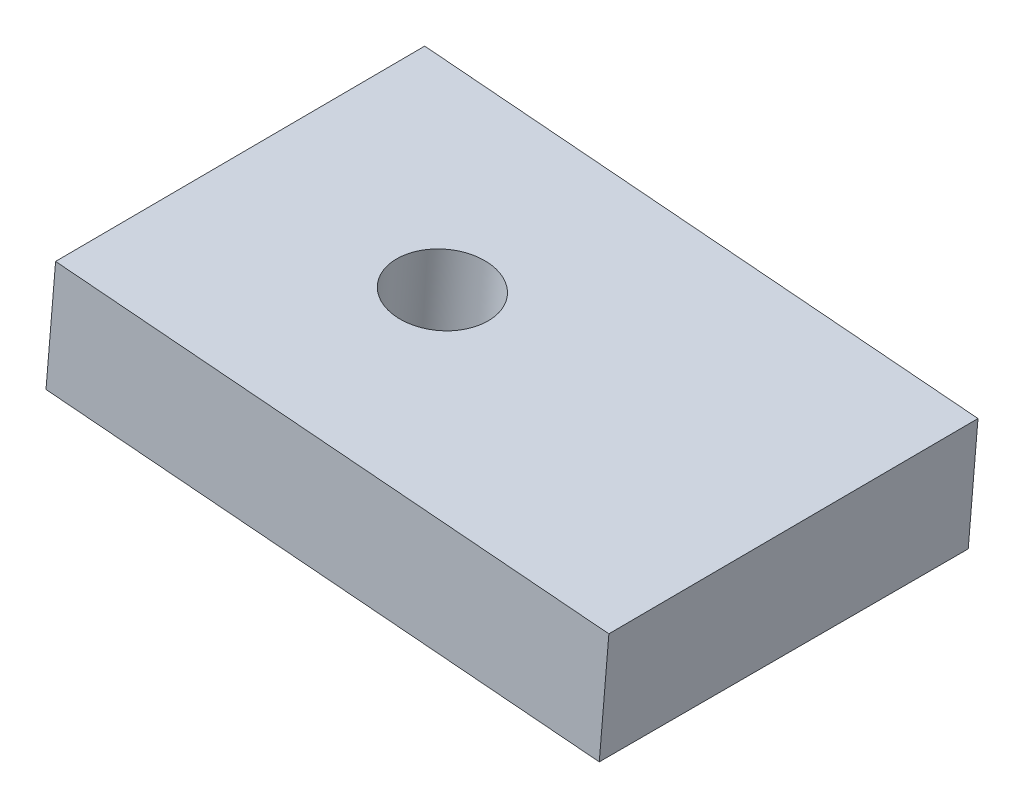
SolidWorks part; units mm, degrees
material "6061 Alloy"
ref_plane "Front" through (0, 0, 0) normal (0, 0, 1) x (1, 0, 0)
ref_plane "Top" through (0, 0, 0) normal (0, 1, 0) x (1, 0, 0)
ref_plane "Right" through (0, 0, 0) normal (1, 0, 0) x (0, 0, -1)
ref_plane "Plane1" through (-1.3154, -15.8621, 0) normal (-0.0826, -0.9966, 0) x (0.9966, -0.0826, 0)
sketch "Sketch1" plane through (-1.3154, -15.8621, 0) normal (-0.0826, -0.9966, 0) x (0.9966, -0.0826, 0)
  line L0 (-9.1777, 10) -> (-24.2253, 10)
  line L1 (-24.2253, 10) -> (-24.2253, 0)
  line L2 (-24.2253, 0) -> (-9.1777, 0)
  line L3 (-9.1777, 0) -> (-9.1777, 10)
extrude "Boss-Extrude1" add sketch "Sketch1" against normal blind 3.147
draft "Draft1" type of draft neutral plane draft angle 0.326 faces to draft 1 face at (-17.6996, -11.3456, 5) neutral plane through (-10.2016, -11.9674, 10) neutral plane normal (0, 0, 1) parameters "D1"=0.326
ref_plane "Plane2" through (-1.0524, -12.6904, 0) normal (0.0826, 0.9966, 0) x (0.9966, -0.0826, 0)
hole_wizard "M3x0.5 Tapped Hole1" positions "Sketch3" profile "Sketch2" tap size "M3x0.5" standard "ANSI Metric" end condition through all
sketch "Sketch3" plane through (-1.0524, -12.6904, 0) normal (0.0826, 0.9966, 0) x (0.9966, -0.0826, 0)
  point P0 (-18.7253, -5)
sketch "Sketch2" plane through (-19.7136, -11.143, 5) normal (0, 0, 1) x (-0.9966, 0.0826, 0)
  line L0 (0, 0) -> (0, 4.4218)
  line L1 (0, 4.4218) -> (1.25, 4.4218)
  line L2 (1.25, 4.4218) -> (1.25, 0)
  line L5 (1.25, 0) -> (0, 0)
  line L11 (0, -6.35) -> (0, 107.95) construction
  dimension "Thru Tap Drill Dia." = 2.5
  dimension "Thru Tap Drill Depth" = 4.4218
